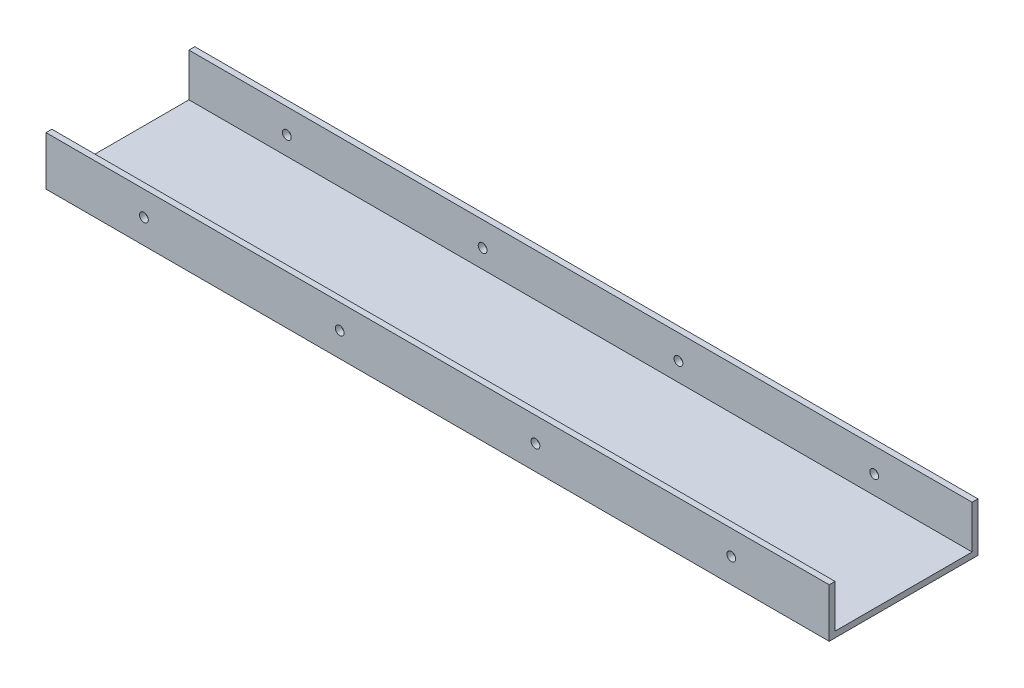
SolidWorks part; units mm, degrees
ref_plane "Plano frontal" through (0, 0, 0) normal (0, 0, 1) x (1, 0, 0)
ref_plane "Plano superior" through (0, 0, 0) normal (0, 1, 0) x (1, 0, 0)
ref_plane "Plano direito" through (0, 0, 0) normal (1, 0, 0) x (0, 0, -1)
sketch "Esboço1" plane through (0, 0, 0) normal (0, 1, 0) x (1, 0, 0)
  line L0 (200, 38) -> (-200, -38) construction
  line L1 (-200, 38) -> (200, 38)
  line L2 (-200, 38) -> (-200, -38)
  line L3 (-200, -38) -> (200, -38)
  line L4 (200, 38) -> (200, -38)
  point P4 (0, 0)
  dimension "D1" = 76
  dimension "D2" = 400
extrude "Ressalto-extrusão1" add sketch "Esboço1" along normal blind 3
sketch "Esboço2" plane through (0, 3, 0) normal (0, 1, 0) x (1, 0, 0)
  line L1 (200, -38) -> (200, 38) construction
  line L2 (-200, 38) -> (200, 38)
  line L3 (-200, 38) -> (-200, 35)
  line L4 (-200, 35) -> (200, 35)
  line L5 (200, 38) -> (200, 35)
  line L7 (-200, -38) -> (200, -38)
  line L8 (-200, -38) -> (-200, -35)
  line L9 (-200, -35) -> (200, -35)
  line L10 (200, -38) -> (200, -35)
  dimension "D1" = 3
  dimension "D2" = 3
extrude "Ressalto-extrusão2" add sketch "Esboço2" along normal blind 22
hole_wizard "Furo com folga de M41" positions "3DSketch1" profile "Esboço3" hole size "M4" standard "ISO" end condition through all
sketch3d "3DSketch1"
  line L0 (-150, 12.5, 38) -> (150, 12.5, 38) construction
  line L2 (-200, 0, 38) -> (200, 0, 38) construction
  line L3 (-200, 25, 38) -> (-200, 0, 38) construction
  line L4 (200, 25, 38) -> (200, 0, 38) construction
  point P0 (-150, 12.5, 38)
  point P4 (150, 12.5, 38)
  point P21 (-50, 12.5, 38)
  point P28 (50, 12.5, 38)
  dimension "D1" = 12.5
  dimension "D2" = 50
  dimension "D3" = 50
  dimension "D4" = 100
  dimension "D5" = 100
sketch "Esboço3" plane through (-150, 12.5, 38) normal (1, 0, 0) x (0, -1, 0)
  line L0 (0, 0) -> (0, 76)
  line L1 (0, 76) -> (2.25, 76)
  line L2 (2.25, 76) -> (2.25, 0)
  line L5 (2.25, 0) -> (0, 0)
  line L11 (0, -6.35) -> (0, 107.95) construction
  dimension "Thru Hole Dia." = 4.5
  dimension "Thru Hole Depth" = 76
